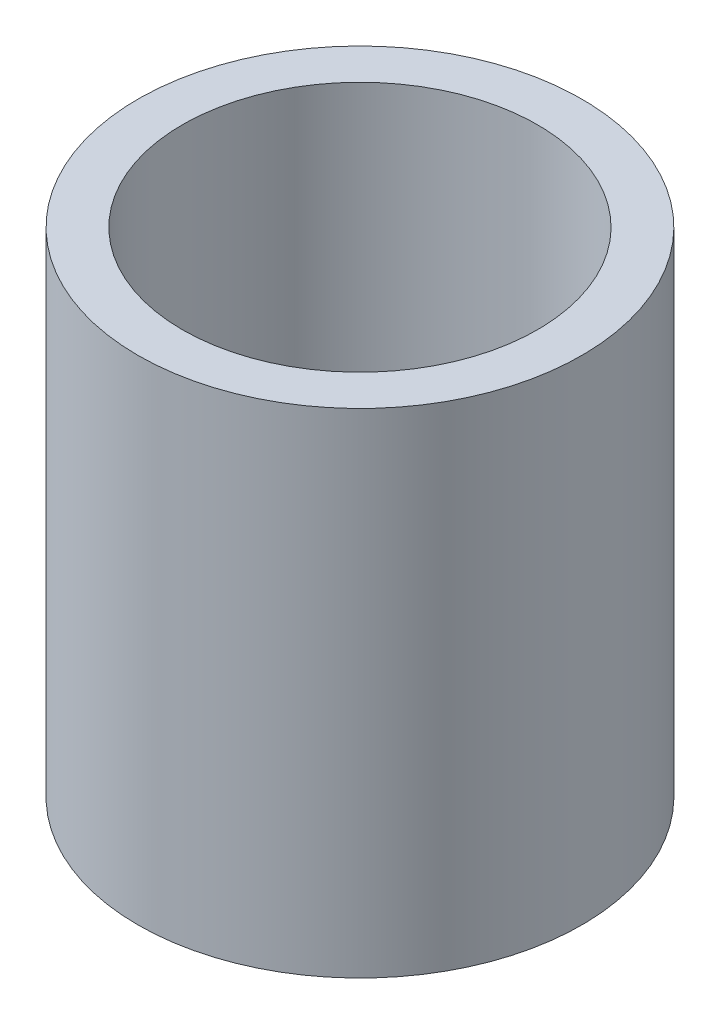
SolidWorks part; units mm, degrees
material "ABS"
ref_plane "前视基准面" through (0, 0, 0) normal (0, 0, 1) x (1, 0, 0)
ref_plane "上视基准面" through (0, 0, 0) normal (0, 1, 0) x (1, 0, 0)
ref_plane "右视基准面" through (0, 0, 0) normal (1, 0, 0) x (0, 0, -1)
other "Configuration Table"
sketch "草图1" plane through (0, 0, 0) normal (0, 1, 0) x (1, 0, 0)
  circle A0 centre (0, 0) radius 2.25
  circle A1 centre (0, 0) radius 1.8
  dimension "D1" = 4.5
  dimension "D2" = 3.6
extrude "凸台-拉伸1" add sketch "草图1" along normal blind 5
